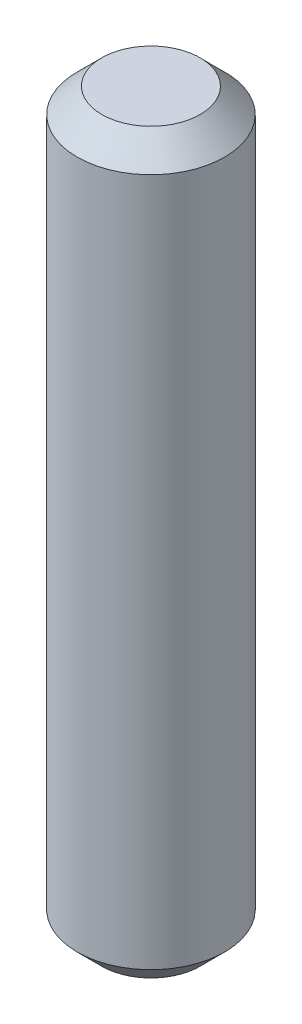
SolidWorks part; units mm, degrees
material "1.0553 (S355J0)"
ref_plane "Front Plane" through (0, 0, 0) normal (0, 0, 1) x (1, 0, 0)
ref_plane "Top Plane" through (0, 0, 0) normal (0, 1, 0) x (1, 0, 0)
ref_plane "Right Plane" through (0, 0, 0) normal (1, 0, 0) x (0, 0, -1)
sketch "Sketch1" plane through (0, 0, 0) normal (0, 1, 0) x (1, 0, 0)
  circle A0 centre (0, 0) radius 1.5
  dimension "D1" = 3
extrude "Boss-Extrude1" add sketch "Sketch1" along normal blind 15
chamfer "Chamfer1" distance 0.5 angle 45 2 edges at (0, 0, 1.5) (0, 15, 1.5)
